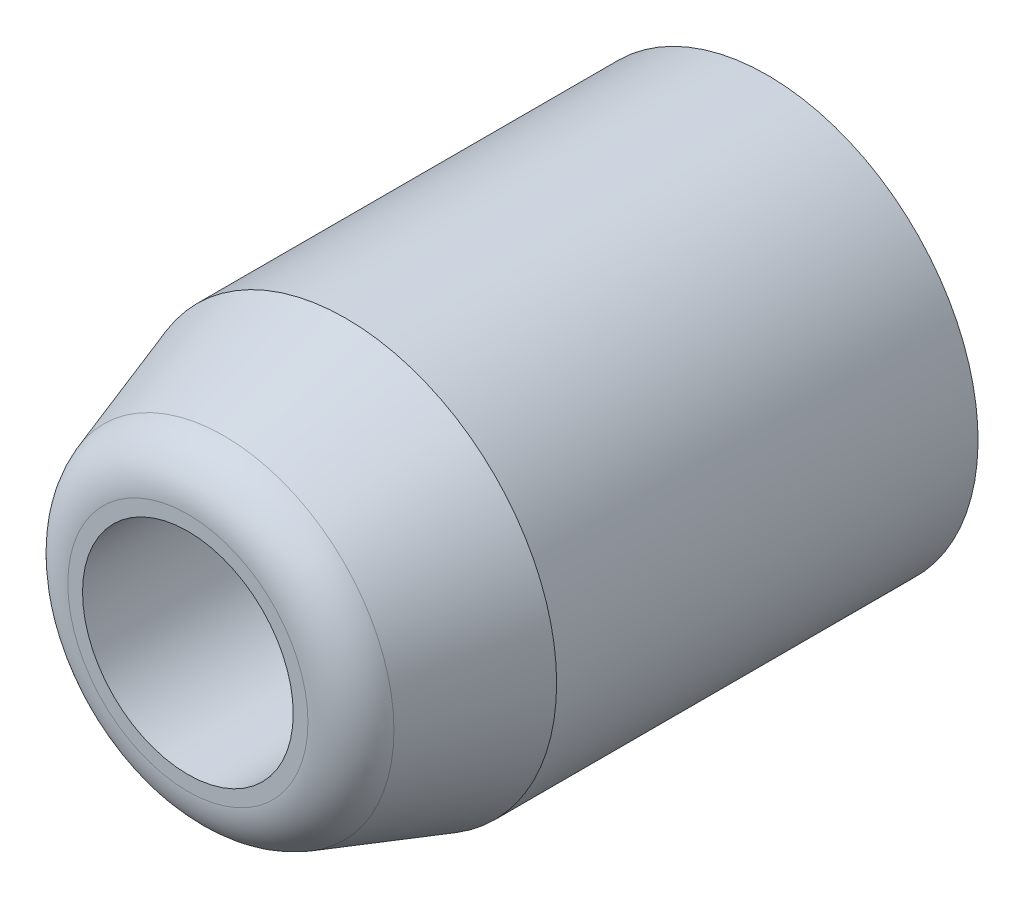
SolidWorks part; units mm, degrees
ref_plane "Front" through (0, 0, 0) normal (0, 0, 1) x (1, 0, 0)
ref_plane "Top" through (0, 0, 0) normal (0, 1, 0) x (1, 0, 0)
ref_plane "Right" through (0, 0, 0) normal (1, 0, 0) x (0, 0, -1)
sketch "Sketch1" plane through (0, 0, 0) normal (0, 0, 1) x (1, 0, 0)
  circle A0 centre (0, 0) radius 3
  circle A1 centre (0, 0) radius 4
  point P3 (0, 0)
  dimension "D1" = 6
  dimension "D2" = 1
extrude "Boss-Extrude1" add sketch "Sketch1" along normal blind 8
sketch "Sketch2" plane through (0, 0, 8) normal (0, 0, 1) x (1, 0, 0)
  circle A0 centre (0, 0) radius 4
  circle A1 centre (0, 0) radius 3
  circle A2 centre (0, 0) radius 3 construction
  circle A3 centre (0, 0) radius 4 construction
  point P3 (0, 0)
ref_plane "Plane1" through (0, 0, 11) normal (0, 0, 1) x (1, 0, 0)
sketch "Sketch3" plane through (0, 0, 11) normal (0, 0, 1) x (1, 0, 0)
  circle A0 centre (0, 0) radius 2
  circle A1 centre (0, 0) radius 3
  point P3 (0, 0)
  point P4 (0, 0)
  dimension "D1" = 4
  dimension "D2" = 1
loft "Loft1" add section "Sketch2" section "Sketch3"
sketch "Sketch4" plane through (0, 0, 11) normal (0, 0, 1) x (1, 0, 0)
  circle A0 centre (0, 0) radius 2
  dimension "D1" = 4
extrude "Cut-Extrude1" cut sketch "Sketch4" against normal through all
fillet "Fillet1" radius 1 1 edges at (3, 0, 11)
sketch "Sketch5" plane through (0, 0, 0) normal (0, 1, 0) x (1, 0, 0)
  line L1 (-3, 0) -> (2, 0)
  line L2 (-3, 0) -> (-3, -2)
  line L3 (-3, -2) -> (2, -2)
  line L4 (2, 0) -> (2, -2)
  dimension "D1" = 2
  dimension "D2" = 5
extrude "Cut-Extrude2" cut sketch "Sketch5" against normal blind 6
